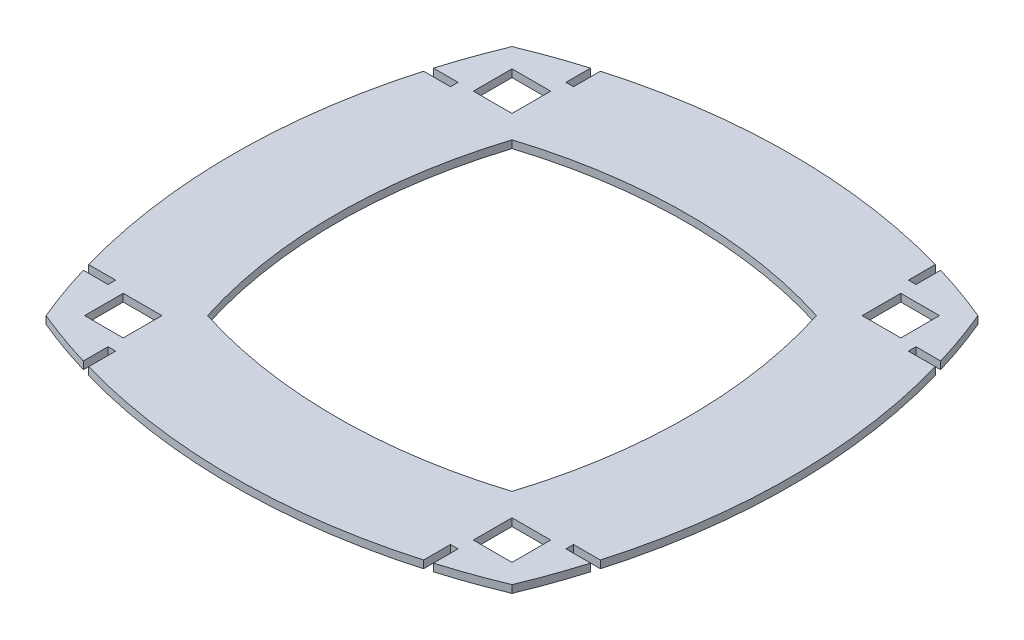
SolidWorks part; units mm, degrees
ref_plane "Front Plane" through (0, 0, 0) normal (0, 0, 1) x (1, 0, 0)
ref_plane "Top Plane" through (0, 0, 0) normal (0, 1, 0) x (1, 0, 0)
ref_plane "Right Plane" through (0, 0, 0) normal (1, 0, 0) x (0, 0, -1)
sketch "Sketch1" plane through (0, 0, 0) normal (0, 1, 0) x (1, 0, 0)
  line L0 (115, 140.4) -> (115, 115)
  line L1 (-153.065, 153.065) -> (153.065, 153.065) construction
  line L2 (-153.065, 153.065) -> (-153.065, -153.065) construction
  line L3 (-153.065, -153.065) -> (153.065, -153.065) construction
  line L4 (153.065, 153.065) -> (153.065, -153.065) construction
  line L5 (0, -153.065) -> (0, 153.065) construction
  line L6 (-153.065, 0) -> (153.065, 0) construction
  line L7 (-140.4, 140.4) -> (140.4, 140.4) construction
  line L8 (-140.4, 140.4) -> (-140.4, -140.4) construction
  line L9 (-140.4, -140.4) -> (140.4, -140.4) construction
  line L10 (140.4, 140.4) -> (140.4, -140.4) construction
  line L11 (0, -140.4) -> (0, 140.4) construction
  line L12 (-140.4, 0) -> (140.4, 0) construction
  line L13 (-140.4, 140.4) -> (-115, 140.4)
  line L14 (-140.4, 140.4) -> (-140.4, 115)
  line L15 (-140.4, 115) -> (-115, 115)
  line L16 (-115, 140.4) -> (-115, 115)
  line L17 (140.4, 140.4) -> (115, 140.4)
  line L18 (140.4, 140.4) -> (140.4, 115)
  line L19 (140.4, 115) -> (115, 115)
  line L20 (140.4, -140.4) -> (140.4, -115)
  line L21 (140.4, -140.4) -> (115, -140.4)
  line L22 (115, -140.4) -> (115, -115)
  line L23 (140.4, -115) -> (115, -115)
  line L24 (-115, -140.4) -> (-115, -115)
  line L25 (-140.4, -140.4) -> (-115, -140.4)
  line L26 (-140.4, -140.4) -> (-140.4, -115)
  line L27 (-140.4, -115) -> (-115, -115)
  line L28 (115, 150.4) -> (110, 150.4)
  line L29 (-100, 100) -> (100, 100) construction
  line L30 (-100, 100) -> (-100, -100) construction
  line L31 (-100, -100) -> (100, -100) construction
  line L32 (100, 100) -> (100, -100) construction
  line L33 (0, -100) -> (0, 100) construction
  line L34 (-100, 0) -> (100, 0) construction
  line L35 (-115, 150.4) -> (-110, 150.4)
  line L36 (-115, 150.4) -> (-115, 166.622)
  line L37 (110, 150.4) -> (110, 168.0874)
  line L38 (-110, 150.4) -> (-110, 168.0874)
  line L39 (-150.4, 115) -> (-166.622, 115)
  line L40 (-150.4, 115) -> (-150.4, 110)
  line L41 (-150.4, 110) -> (-168.0874, 110)
  line L42 (115, 150.4) -> (115, 166.622)
  line L43 (150.4, 115) -> (150.4, 110)
  line L44 (150.4, 115) -> (166.622, 115)
  line L45 (150.4, 110) -> (168.0874, 110)
  line L46 (150.4, -115) -> (150.4, -110)
  line L47 (150.4, -115) -> (166.622, -115)
  line L48 (150.4, -110) -> (168.0874, -110)
  line L49 (115, -150.4) -> (115, -166.622)
  line L50 (110, -150.4) -> (110, -168.0874)
  line L51 (115, -150.4) -> (110, -150.4)
  line L52 (-110, -150.4) -> (-110, -168.0874)
  line L53 (-115, -150.4) -> (-115, -166.622)
  line L54 (-115, -150.4) -> (-110, -150.4)
  line L55 (-150.4, -115) -> (-150.4, -110)
  line L56 (-150.4, -115) -> (-166.622, -115)
  line L57 (-150.4, -110) -> (-168.0874, -110)
  arc A0 (-153.065, 153.065) -> (-115, 166.622) centre (0, -216.4903) cw
  arc A1 (153.065, 153.065) -> (166.622, 115) centre (-216.4903, 0) cw
  arc A2 (153.065, -153.065) -> (115, -166.622) centre (0, 216.4903) cw
  arc A3 (-153.065, -153.065) -> (-166.622, -115) centre (216.4903, 0) cw
  arc A4 (-110, 168.0874) -> (110, 168.0874) centre (0, -216.4903) cw
  arc A5 (-166.622, 115) -> (-153.065, 153.065) centre (216.4903, 0) cw
  arc A6 (168.0874, 110) -> (168.0874, -110) centre (-216.4903, 0) cw
  arc A7 (115, 166.622) -> (153.065, 153.065) centre (0, -216.4903) cw
  arc A8 (166.622, -115) -> (153.065, -153.065) centre (-216.4903, 0) cw
  arc A9 (110, -168.0874) -> (-110, -168.0874) centre (0, 216.4903) cw
  arc A10 (-115, -166.622) -> (-153.065, -153.065) centre (0, 216.4903) cw
  arc A11 (-168.0874, -110) -> (-168.0874, 110) centre (216.4903, 0) cw
  arc A12 (-100, 100) -> (100, 100) centre (0, -216.4903) cw
  arc A13 (100, 100) -> (100, -100) centre (-216.4903, 0) cw
  arc A14 (100, -100) -> (-100, -100) centre (0, 216.4903) cw
  arc A15 (-100, -100) -> (-100, 100) centre (216.4903, 0) cw
  point P0 (0, 0)
  point P8 (0, 0)
  point P24 (0, 0)
  dimension "D2" = 400
  dimension "D1" = 306.13
  dimension "D3" = 280.8
  dimension "D4" = 25.4
  dimension "D5" = 200
  dimension "D6" = 5
  dimension "D7" = 5
  dimension "D8" = 10
  dimension "D9" = 10
extrude "Boss-Extrude1" add sketch "Sketch1" along normal blind 5
